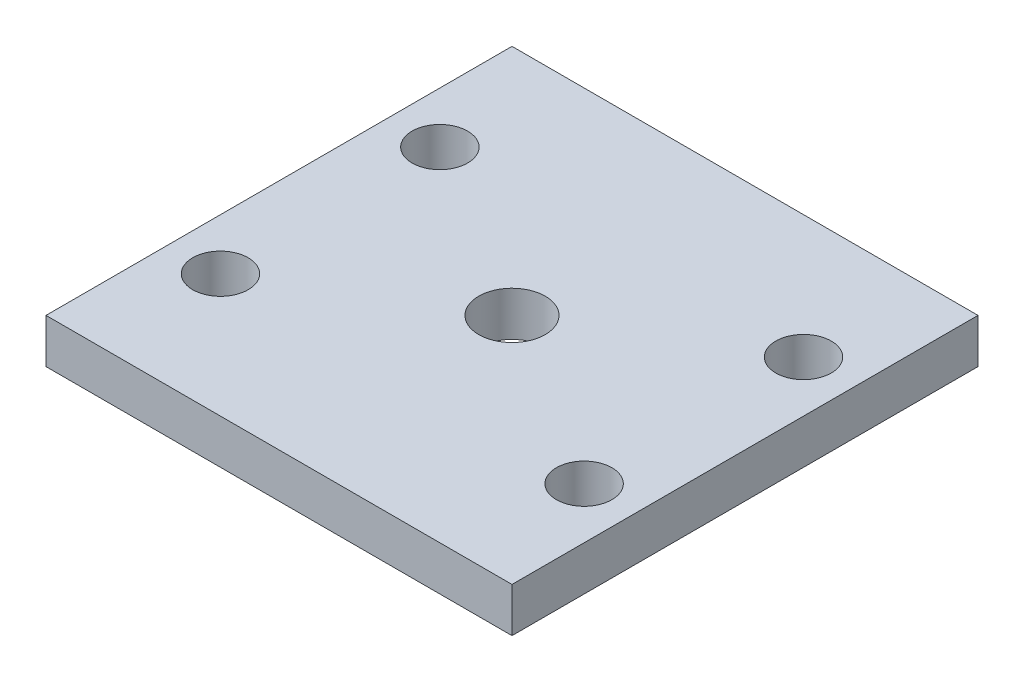
SolidWorks part; units mm, degrees
ref_plane "Front" through (0, 0, 0) normal (0, 0, 1) x (1, 0, 0)
ref_plane "Top" through (0, 0, 0) normal (0, 1, 0) x (1, 0, 0)
ref_plane "Right" through (0, 0, 0) normal (1, 0, 0) x (0, 0, -1)
sketch "Sketch1" plane through (0, 0, 0) normal (0, 1, 0) x (1, 0, 0)
  line L0 (-19.7231, 20.3616) -> (22.2769, 20.3616)
  line L1 (-19.7231, 20.3616) -> (-19.7231, -21.6384)
  line L2 (-19.7231, -21.6384) -> (22.2769, -21.6384)
  line L3 (22.2769, 20.3616) -> (22.2769, -21.6384)
  line L4 (1.2769, -21.6384) -> (1.2769, 20.3616) construction
  line L5 (-19.7231, -0.6384) -> (22.2769, -0.6384) construction
  point P0 (1.2769, -0.6384)
  dimension "D1" = 42
extrude "Boss-Extrude1" add sketch "Sketch1" along normal blind 4
sketch "Sketch2" plane through (0, 4, 0) normal (0, 1, 0) x (1, 0, 0)
  line L0 (-19.7231, 20.3616) -> (-19.7231, -21.6384) construction
  line L1 (22.2769, 20.3616) -> (-19.7231, 20.3616) construction
  circle A0 centre (1.2769, -0.6384) radius 3
  dimension "D1" = 6
  dimension "D2" = 21
  dimension "D3" = 21
extrude "Cut-Extrude1" cut sketch "Sketch2" against normal blind 16
sketch "Sketch4" plane through (0, 4, 0) normal (0, 1, 0) x (1, 0, 0)
  point P0 (-15.112, 9.2485)
  point P1 (-15.112, -10.5254)
  point P3 (17.6657, -10.5254)
  point P5 (17.6657, 9.2485)
hole_wizard "Ø5.0mm Dowel Hole1" positions "Sketch8" profile "Sketch6" hole size "Ø5.0" standard "ANSI Metric"
sketch "Sketch8" plane through (0, 4, 0) normal (0, 1, 0) x (1, 0, 0)
  point P0 (-15.112, -10.5254)
  point P3 (-15.112, 9.2485)
  point P6 (17.6657, 9.2485)
  point P9 (17.6657, -10.5254)
sketch "Sketch6" plane through (-15.112, 4, 10.5254) normal (1, 0, 0) x (0, 0, 1)
  line L0 (0, 0) -> (0, 26.5022)
  line L1 (0, 26.5022) -> (2.5, 25)
  line L2 (2.5, 25) -> (2.5, 0)
  line L5 (2.5, 0) -> (0, 0)
  line L10 (0, 26.5022) -> (-2.5, 25) construction
  line L11 (0, -6.35) -> (0, 107.95) construction
  dimension "Hole Dia." = 5
  dimension "Hole Depth" = 25
  dimension "Drill Angle" = 118
